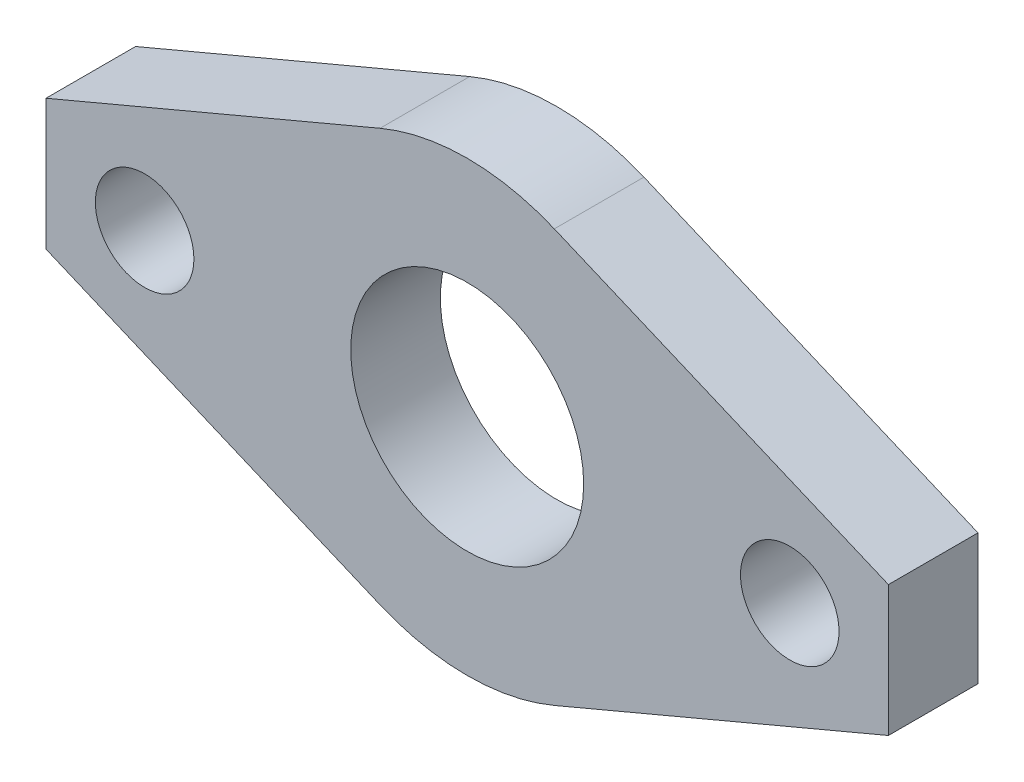
SolidWorks part; units mm, degrees
ref_plane "Front Plane" through (0, 0, 0) normal (0, 0, 1) x (1, 0, 0)
ref_plane "Top Plane" through (0, 0, 0) normal (0, 1, 0) x (1, 0, 0)
ref_plane "Right Plane" through (0, 0, 0) normal (1, 0, 0) x (0, 0, -1)
sketch "Sketch1" plane through (0, 0, 0) normal (0, 0, 1) x (1, 0, 0)
  line L0 (0, 34.35) -> (0, 0) construction
  line L1 (-18, 16) -> (18, 16) construction
  line L2 (-23.5037, 19.6467) -> (-23.5037, 12.3533)
  line L3 (4.8611, 4.4839) -> (23.5037, 12.3533)
  line L4 (-4.8611, 27.5161) -> (-23.5037, 19.6467)
  line L6 (-4.8611, 4.4839) -> (-23.5037, 12.3533)
  line L7 (4.8611, 27.5161) -> (23.5037, 19.6467)
  line L8 (23.5037, 19.6467) -> (23.5037, 12.3533)
  circle A0 centre (0, 0) radius 3.175 construction
  circle A1 centre (0, 16) radius 15 construction
  circle A2 centre (0, 16) radius 6.5
  circle A3 centre (0, 16) radius 12.5 construction
  circle A4 centre (-18, 16) radius 2.75
  circle A5 centre (18, 16) radius 2.75
  circle A6 centre (18, 16) radius 5.5 construction
  arc A7 (-4.8611, 4.4839) -> (4.8611, 4.4839) centre (0, 16) ccw
  arc A8 (-4.8611, 27.5161) -> (4.8611, 27.5161) centre (0, 16) cw
  dimension "D1" = 16
extrude "Boss-Extrude1" add sketch "Sketch1" along normal blind 5
